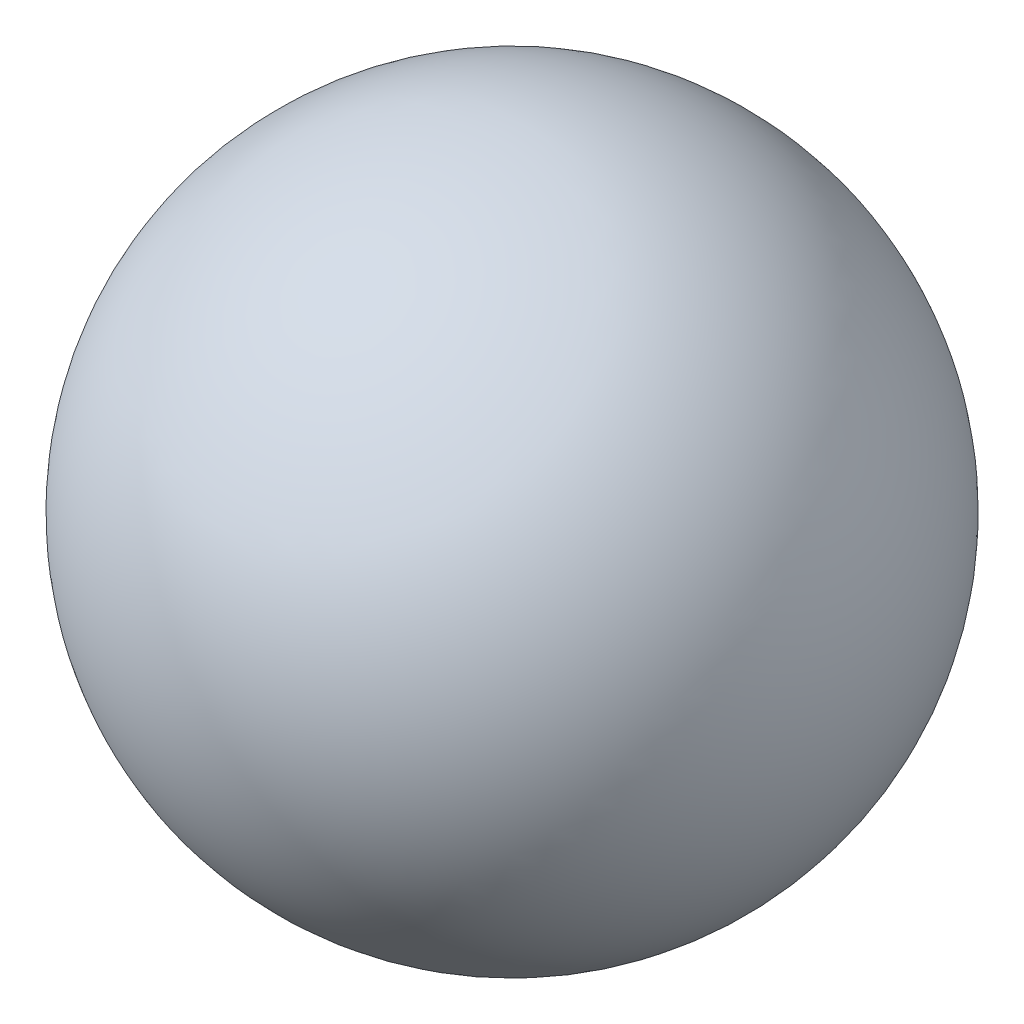
SolidWorks part; units mm, degrees
ref_plane "Plano frontal" through (0, 0, 0) normal (0, 0, 1) x (1, 0, 0)
ref_plane "Plano superior" through (0, 0, 0) normal (0, 1, 0) x (1, 0, 0)
ref_plane "Plano direito" through (0, 0, 0) normal (1, 0, 0) x (0, 0, -1)
sketch "Esboço1" plane through (0, 0, 0) normal (0, 1, 0) x (1, 0, 0)
  line L0 (0, 0) -> (0, 50)
  arc A0 (0, 0) -> (0, 50) centre (0, 25) cw
  dimension "D1" = 50
revolve "Revolução1" add sketch "Esboço1" angle 360 about L0
